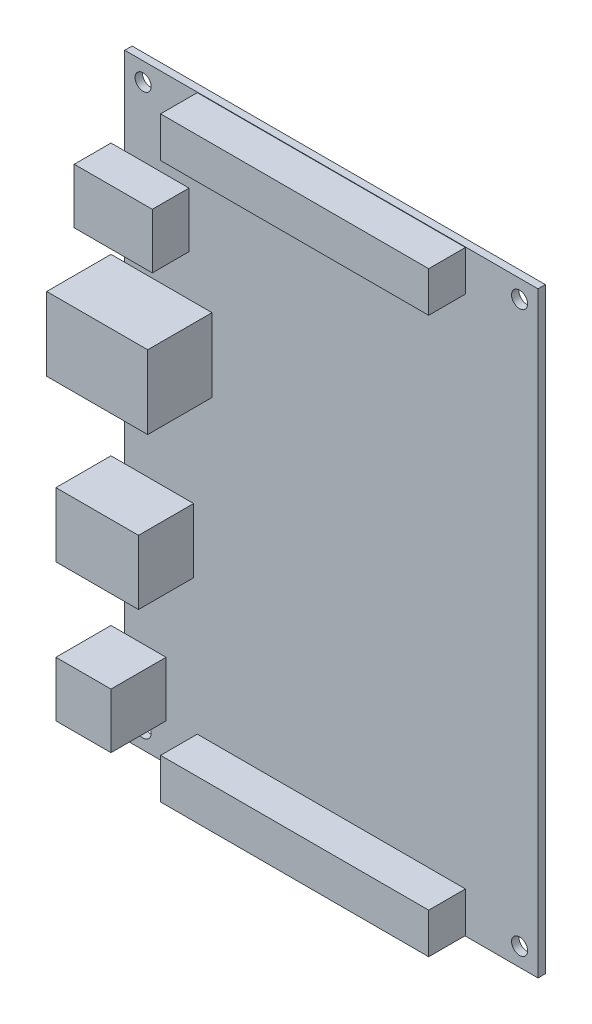
SolidWorks part; units mm, degrees
ref_plane "前视基准面" through (0, 0, 0) normal (0, 0, 1) x (1, 0, 0)
ref_plane "上视基准面" through (0, 0, 0) normal (0, 1, 0) x (1, 0, 0)
ref_plane "右视基准面" through (0, 0, 0) normal (1, 0, 0) x (0, 0, -1)
other "Configuration Table"
sketch "草图1" plane through (0, 0, 0) normal (0, 0, 1) x (1, 0, 0)
  line L1 (-45, -142) -> (45, -142)
  line L2 (-45, -142) -> (-45, -12)
  line L3 (-45, -12) -> (45, -12)
  line L4 (45, -142) -> (45, -12)
  circle A0 centre (-41, -138) radius 1.75
  circle A1 centre (41, -138) radius 1.75
  circle A2 centre (41, -16) radius 1.75
  circle A3 centre (-41, -16) radius 1.75
extrude "AX_PCB_flat_front_compartment" add sketch "草图1" along normal blind 1.6 from offset 25
sketch "草图2" plane through (0, 0, 0) normal (0, 0, 1) x (1, 0, 0)
  line L1 (-29.2, -141.9) -> (29.2, -141.9)
  line L2 (-29.2, -141.9) -> (-29.2, -133.1)
  line L3 (-29.2, -133.1) -> (29.2, -133.1)
  line L4 (29.2, -141.9) -> (29.2, -133.1)
extrude "J10_front_camera_header" add sketch "草图2" along normal blind 8 from offset 26.6
sketch "草图3" plane through (0, 0, 0) normal (0, 0, 1) x (1, 0, 0)
  line L1 (-29.2, -20.9) -> (29.2, -20.9)
  line L2 (-29.2, -20.9) -> (-29.2, -12.1)
  line L3 (-29.2, -12.1) -> (29.2, -12.1)
  line L4 (29.2, -20.9) -> (29.2, -12.1)
extrude "J11_rear_IDC40" add sketch "草图3" along normal blind 8 from offset 26.6
sketch "草图4" plane through (0, 0, 0) normal (0, 0, 1) x (1, 0, 0)
  line L1 (-48, -134) -> (-34, -134)
  line L2 (-48, -134) -> (-48, -122)
  line L3 (-48, -122) -> (-34, -122)
  line L4 (-34, -134) -> (-34, -122)
sketch "草图5" plane through (0, 0, 0) normal (0, 0, 1) x (1, 0, 0)
  line L1 (-48, -43) -> (-31, -43)
  line L2 (-48, -43) -> (-48, -31)
  line L3 (-48, -31) -> (-31, -31)
  line L4 (-31, -43) -> (-31, -31)
extrude "HDMI_left" add sketch "草图5" along normal blind 8 from offset 26.6
sketch "草图6" plane through (0, 0, 0) normal (0, 0, 1) x (1, 0, 0)
  line L1 (-48, -104) -> (-30, -104)
  line L2 (-48, -104) -> (-48, -90)
  line L3 (-48, -90) -> (-30, -90)
  line L4 (-30, -104) -> (-30, -90)
extrude "USB_HOST_left" add sketch "草图6" along normal blind 12 from offset 26.6
sketch "草图7" plane through (0, 0, 0) normal (0, 0, 1) x (1, 0, 0)
  line L1 (-48, -68) -> (-26, -68)
  line L2 (-48, -68) -> (-48, -52)
  line L3 (-48, -52) -> (-26, -52)
  line L4 (-26, -68) -> (-26, -52)
extrude "RJ45_left" add sketch "草图7" along normal blind 14 from offset 26.6
sketch "草图8" plane through (0, 0, 0) normal (0, 0, 1) x (1, 0, 0)
  line L1 (-48, -134) -> (-36, -134)
  line L2 (-48, -134) -> (-48, -122)
  line L3 (-48, -122) -> (-36, -122)
  line L4 (-36, -134) -> (-36, -122)
extrude "DC5521_approx_body_clear_camera_edge" add sketch "草图8" along normal blind 12 from offset 26.6
